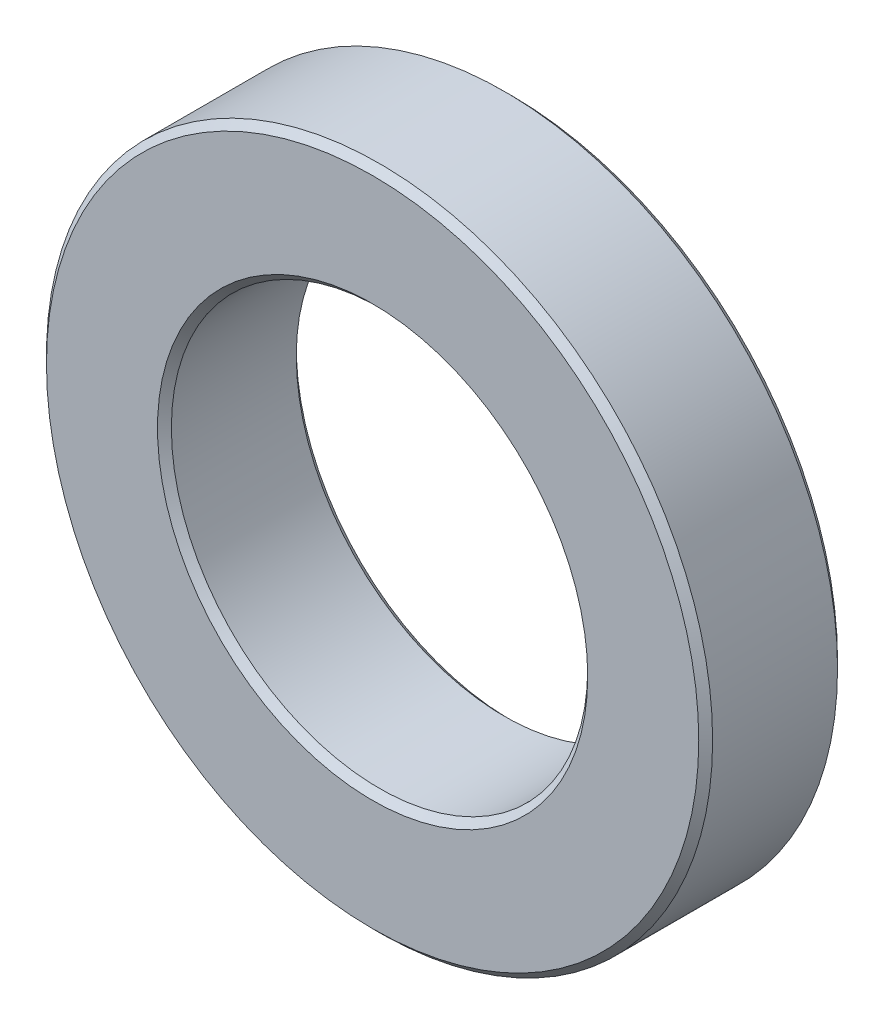
SolidWorks part; units mm, degrees
material "Сплав 1060"
ref_plane "Спереди" through (0, 0, 0) normal (0, 0, 1) x (1, 0, 0)
ref_plane "Сверху" through (0, 0, 0) normal (0, 1, 0) x (1, 0, 0)
ref_plane "Справа" through (0, 0, 0) normal (1, 0, 0) x (0, 0, -1)
sketch "Эскиз1" plane through (0, 0, 0) normal (0, 0, 1) x (1, 0, 0)
  circle A0 centre (0, 0) radius 7.5
  circle A1 centre (0, 0) radius 12
  dimension "D1" = 15
  dimension "D2" = 24
extrude "Бобышка-Вытянуть1" add sketch "Эскиз1" along normal blind 5
sketch "Эскиз2" [suppressed] plane through (0, 0, 5) normal (0, 0, 1) x (1, 0, 0)
  circle A0 centre (0, 0) radius 2.5 construction
  circle A1 centre (0, 0) radius 2.5
  circle A2 centre (0, 0) radius 9
  dimension "D1" = 18
extrude "Бобышка-Вытянуть2" [suppressed] add sketch "Эскиз2" against normal blind 1
chamfer "Фаска1" [suppressed] distance 0.25 angle 45
chamfer "Фаска2" [suppressed] distance 0.25 angle 45
chamfer "Фаска3" [suppressed] distance 0.25 angle 45
chamfer "Фаска4" [suppressed] distance 0.25 angle 45
chamfer "Фаска5" distance 0.25 angle 45 4 edges at (12, 0, 0) (12, 0, 5) (7.5, 0, 0) (7.5, 0, 5)
